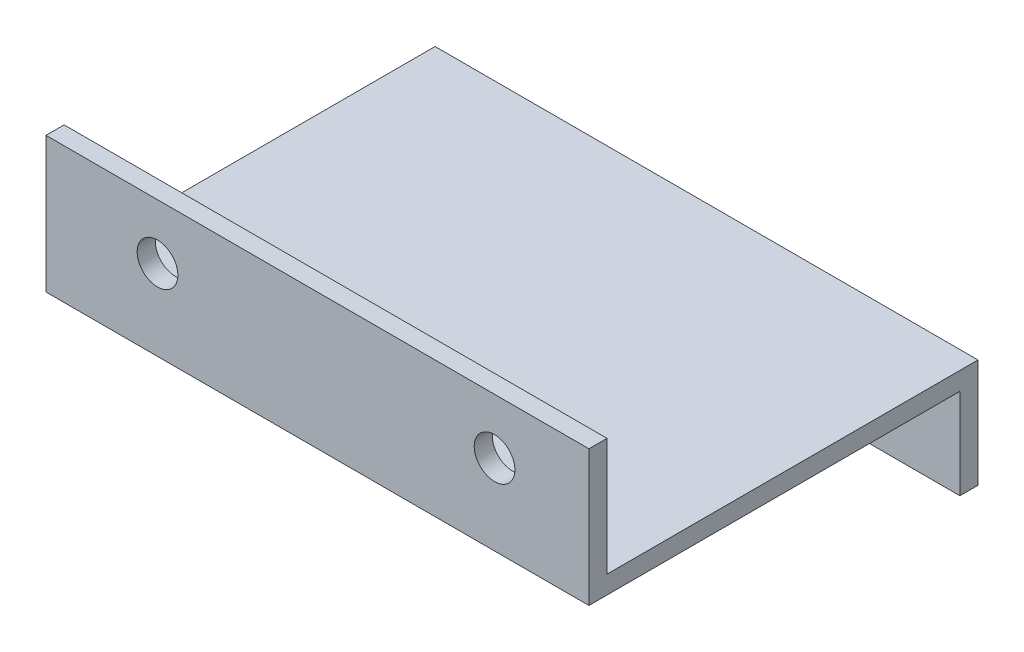
SolidWorks part; units mm, degrees
ref_plane "Front Plane" through (0, 0, 0) normal (0, 0, 1) x (1, 0, 0)
ref_plane "Top Plane" through (0, 0, 0) normal (0, 1, 0) x (1, 0, 0)
ref_plane "Right Plane" through (0, 0, 0) normal (1, 0, 0) x (0, 0, -1)
sketch "Sketch1" plane through (0, 0, 0) normal (0, 0, 1) x (1, 0, 0)
  line L1 (-30, -10) -> (30, -10)
  line L2 (-30, -10) -> (-30, 10)
  line L3 (-30, 10) -> (30, 10)
  line L4 (30, -10) -> (30, 10)
  line L5 (-30, -10) -> (30, 10) construction
  line L6 (-30, 10) -> (30, -10) construction
  point P0 (0, 0)
  dimension "D1" = 60
  dimension "D2" = 20
extrude "Boss-Extrude1" add sketch "Sketch1" along normal blind 43
sketch "Sketch2" plane through (0, 0, 0) normal (0, 0, -1) x (-1, 0, 0)
  line L0 (-30, 10) -> (30, 10)
  line L1 (-30, 10) -> (-30, 2)
  line L2 (30, 10) -> (30, 2)
  line L3 (-30, 2) -> (30, 2)
  dimension "D1" = 8
extrude "Cut-Extrude1" cut sketch "Sketch2" against normal blind 41
sketch "Sketch3" plane through (0, 0, 43) normal (0, 0, 1) x (1, 0, 0)
  line L0 (30, -10) -> (-30, -10)
  line L1 (30, -10) -> (30, 0)
  line L2 (-30, -10) -> (-30, 0)
  line L3 (30, 0) -> (-30, 0)
  dimension "D1" = 10
extrude "Cut-Extrude2" cut sketch "Sketch3" against normal blind 41
sketch "Sketch4" plane through (0, 10, 0) normal (0, 1, 0) x (1, 0, 0)
  line L8 (30, -41) -> (-30, -41)
  line L9 (-30, -41) -> (-30, -43)
  line L10 (-30, -43) -> (30, -43)
  line L11 (30, -43) -> (30, -41)
  line L12 (30, -41) -> (-30, -41)
  line L13 (-30, -41) -> (-30, -43)
  line L14 (-30, -43) -> (30, -43)
  line L15 (30, -43) -> (30, -41)
  dimension "D1" = 0
extrude "Boss-Extrude2" add sketch "Sketch4" along normal blind 5
hole_wizard "M4 Clearance Hole1" positions "Sketch7" profile "Sketch5" hole size "M4" standard "ANSI Metric" end condition through all
sketch "Sketch7" plane through (0, 0, 41) normal (0, 0, -1) x (-1, 0, 0)
  point P0 (-19.5712, 8.8937)
  point P2 (17.6762, 8.8937)
sketch "Sketch5" plane through (19.5712, 8.8937, 41) normal (1, 0, 0) x (0, 1, 0)
  line L0 (0, 0) -> (0, 2)
  line L1 (0, 2) -> (2.25, 2)
  line L2 (2.25, 2) -> (2.25, 0)
  line L5 (2.25, 0) -> (0, 0)
  line L11 (0, -6.35) -> (0, 107.95) construction
  dimension "Thru Hole Dia." = 4.5
  dimension "Thru Hole Depth" = 2
